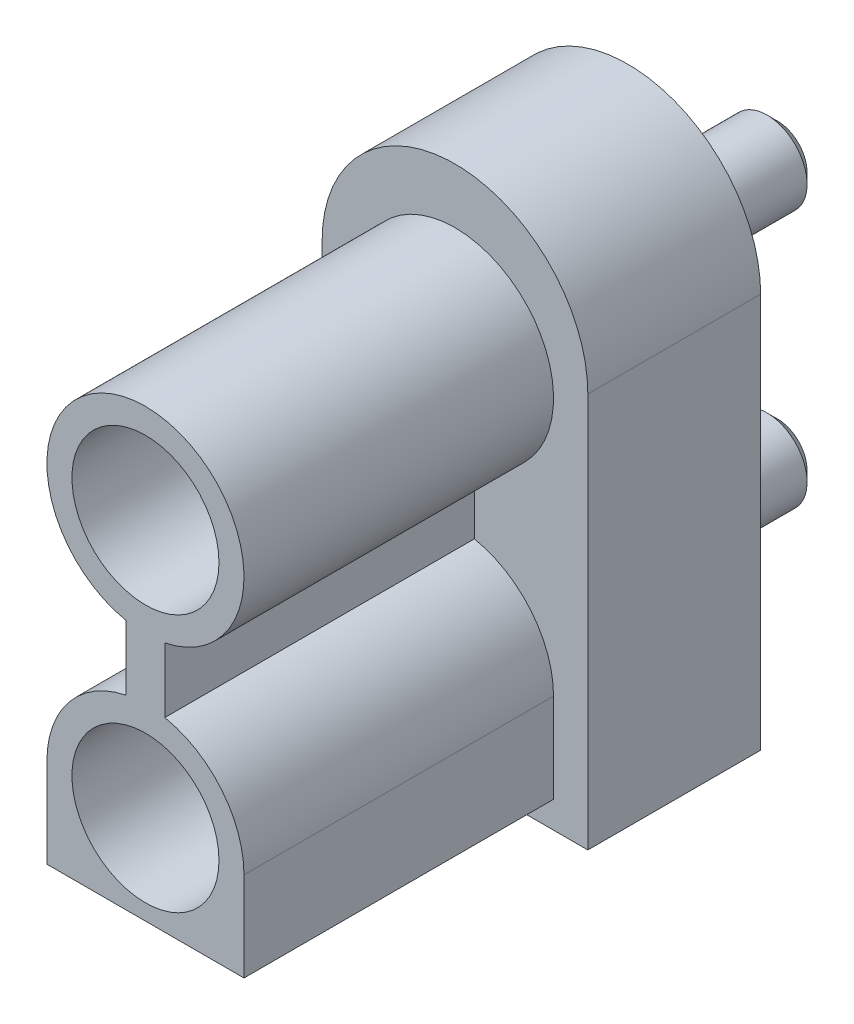
SolidWorks part; units mm, degrees
ref_plane "Alzado" through (0, 0, 0) normal (0, 0, 1) x (1, 0, 0)
ref_plane "Planta" through (0, 0, 0) normal (0, 1, 0) x (1, 0, 0)
ref_plane "Vista lateral" through (0, 0, 0) normal (1, 0, 0) x (0, 0, -1)
sketch "Croquis1" plane through (0, 0, 0) normal (0, 0, 1) x (1, 0, 0)
  line L0 (-2.575, 7.655) -> (-2.575, 0)
  line L1 (-2.575, 0) -> (2.575, 0)
  line L2 (2.575, 0) -> (2.575, 7.655)
  arc A0 (-2.575, 7.655) -> (2.575, 7.655) centre (0, 7.655) cw
  point P4 (0, 0)
  point P7 (0, 10.23)
  dimension "D1" = 5.15
  dimension "D2" = 10.23
extrude "Saliente-Extruir1" add sketch "Croquis1" along normal blind 3.35
sketch "Croquis2" plane through (0, 0, 0) normal (0, 0, -1) x (-1, 0, 0)
  line L0 (2.575, 0) -> (-2.575, 0) construction
  circle A0 centre (0, 7.25) radius 0.775
  circle A1 centre (0, 2.25) radius 0.775
  point P8 (0.5164, 9.127)
  dimension "D1" = 1.55
  dimension "D2" = 5
  dimension "D3" = 2.25
extrude "Saliente-Extruir2" add sketch "Croquis2" along normal blind 2.9
chamfer "Chaflán1" distance 0.2 angle 45 2 edges at (-0.775, 2.25, -2.9) (-0.775, 7.25, -2.9)
sketch "Croquis3" plane through (0, 0, 3.35) normal (0, 0, 1) x (1, 0, 0)
  line L0 (-1.91, 2.25) -> (-1.91, 0.5186)
  line L1 (-1.91, 0.5186) -> (1.91, 0.5186)
  line L2 (1.91, 0.5186) -> (1.91, 2.25)
  line L3 (0.375, 5.3772) -> (0.375, 4.1228)
  line L4 (-0.375, 5.3772) -> (-0.375, 4.1228)
  line L5 (0, 8.2519) -> (0, 1.7332) construction
  line L6 (-2.575, 0) -> (2.575, 0) construction
  arc A0 (-1.91, 2.25) -> (-0.375, 4.1228) centre (0, 2.25) cw
  circle A1 centre (0, 2.25) radius 1.425
  circle A2 centre (0, 7.25) radius 1.425
  arc A3 (0.375, 5.3772) -> (-0.375, 5.3772) centre (0, 7.25) ccw
  arc A4 (0.375, 4.1228) -> (1.91, 2.25) centre (0, 2.25) cw
  dimension "D1" = 2.85
  dimension "D2" = 3.82
  dimension "D3" = 0.75
  dimension "D4" = 5
  dimension "D5" = 2.25
extrude "Saliente-Extruir3" add sketch "Croquis3" along normal blind 6
